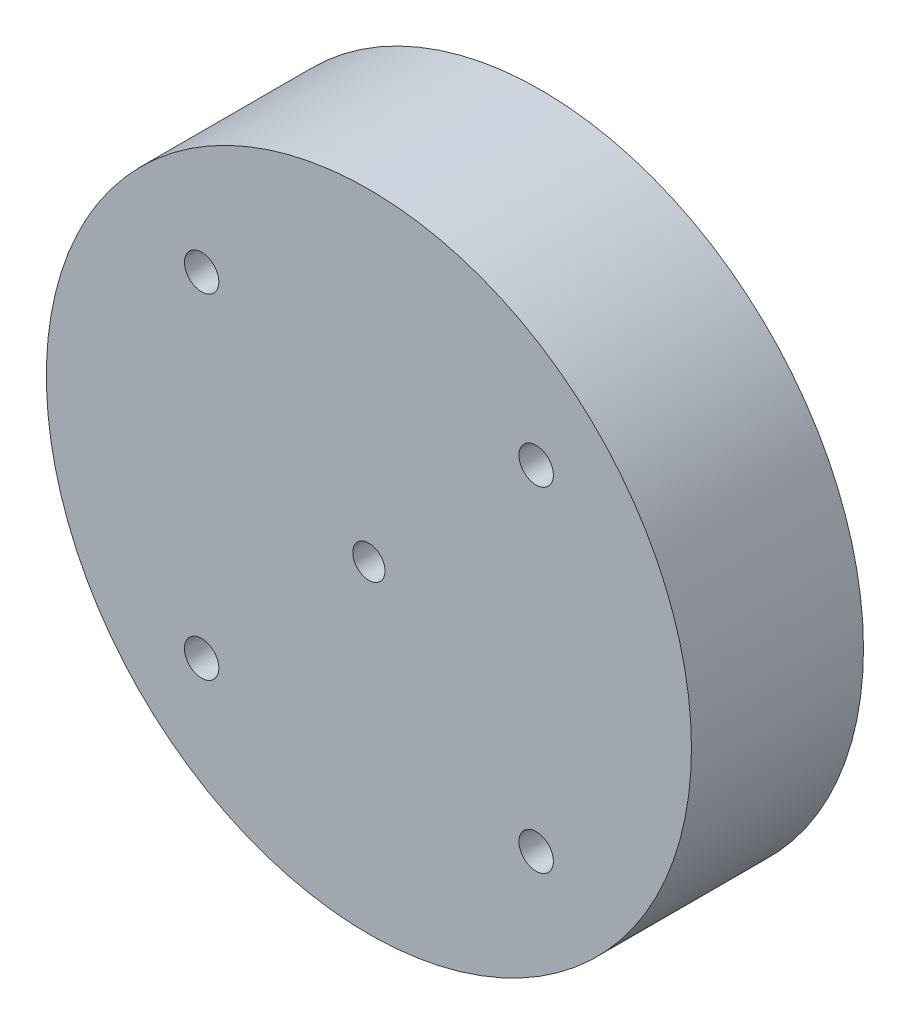
SolidWorks part; units mm, degrees
ref_plane "Front Plane" through (0, 0, 0) normal (0, 0, 1) x (1, 0, 0)
ref_plane "Top Plane" through (0, 0, 0) normal (0, 1, 0) x (1, 0, 0)
ref_plane "Right Plane" through (0, 0, 0) normal (1, 0, 0) x (0, 0, -1)
sketch "Sketch1" plane through (0, 0, 0) normal (0, 0, 1) x (1, 0, 0)
  circle A0 centre (0, 0) radius 30
  circle A1 centre (0, 0) radius 1.5
extrude "Boss-Extrude1" add sketch "Sketch1" along normal blind 16
sketch "Sketch2" plane through (0, 0, 0) normal (0, 0, 1) x (1, 0, 0)
  circle A0 centre (15.5563, 15.5563) radius 1.6
  circle A1 centre (-15.5563, 15.5563) radius 1.6
  circle A2 centre (-15.5563, -15.5563) radius 1.6
  circle A3 centre (15.5563, -15.5563) radius 1.6
extrude "Cut-Extrude2" cut sketch "Sketch2" along normal blind 17
